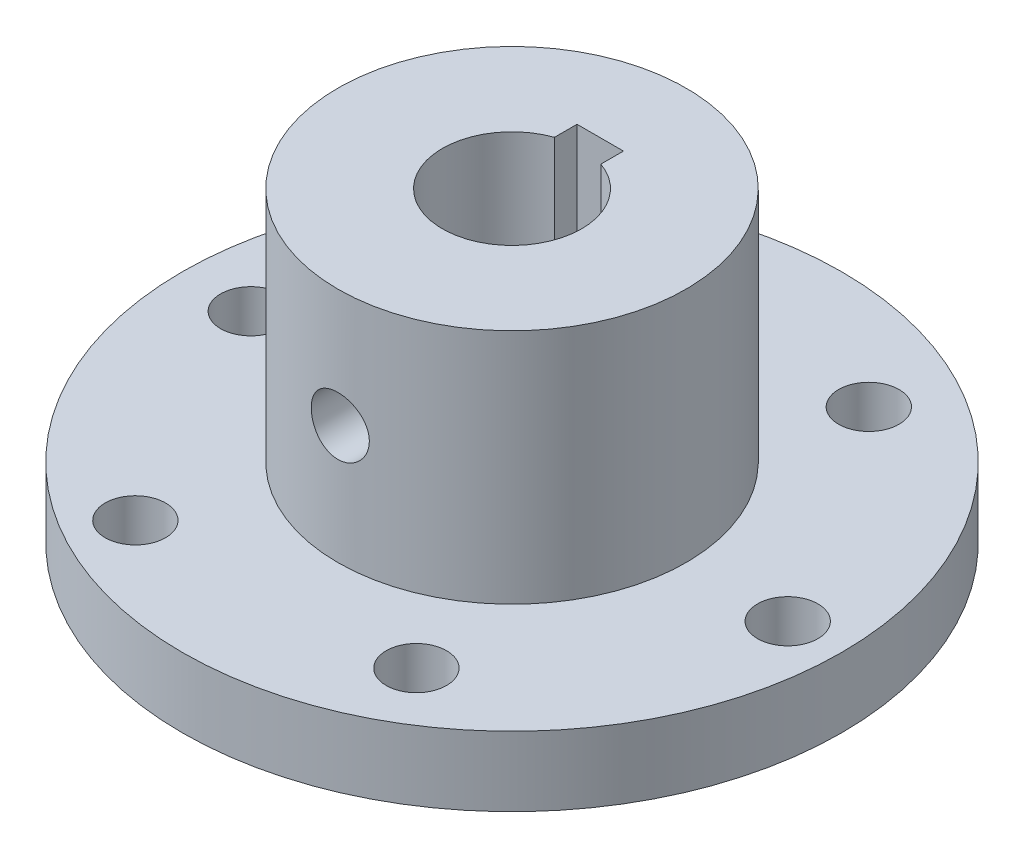
SolidWorks part; units mm, degrees
ref_plane "前视基准面" through (0, 0, 0) normal (0, 0, 1) x (1, 0, 0)
ref_plane "上视基准面" through (0, 0, 0) normal (0, 1, 0) x (1, 0, 0)
ref_plane "右视基准面" through (0, 0, 0) normal (1, 0, 0) x (0, 0, -1)
sketch "Sketch1" plane through (0, 0, 0) normal (1, 0, 0) x (0, 0, -1)
  line L0 (6, 0) -> (28.4, 0)
  line L1 (28.4, 0) -> (28.4, 6)
  line L2 (28.4, 6) -> (15, 6)
  line L3 (15, 6) -> (15, 26.4)
  line L4 (15, 26.4) -> (6, 26.4)
  line L5 (6, 26.4) -> (6, 0)
  line L6 (0, 21.7671) -> (0, -3.5767) construction
  dimension "D1" = 6
  dimension "D2" = 15
  dimension "D3" = 28.4
  dimension "D4" = 6
  dimension "D5" = 20.4
revolve "Revolve1" add sketch "Sketch1" angle 360 about L6
sketch "Sketch3" plane through (0, 6, 0) normal (0, 1, 0) x (1, 0, 0)
  circle A0 centre (0, 0) radius 22.5 construction
  circle A1 centre (-22.5, 0) radius 2.6
  circle A2 centre (11.25, 19.4856) radius 2.6
  circle A3 centre (11.25, -19.4856) radius 2.6
  circle A8 centre (0, 0) radius 23.75 construction
  circle A9 centre (23.75, 0) radius 2.6
  circle A10 centre (-11.875, -20.5681) radius 2.6
  circle A11 centre (-11.875, 20.5681) radius 2.6
  dimension "D1" = 45
  dimension "D2" = 5.2
  dimension "D4" = 47.5
  dimension "D5" = 3
  dimension "D3" = 3
extrude "Cut-Extrude2" cut sketch "Sketch3" against normal up to next
sketch "Sketch4" plane through (0, 26.4, 0) normal (0, 1, 0) x (1, 0, 0)
  line L0 (0, -19.1286) -> (0, 23.5515) construction
  line L1 (-5.6768, 7.6) -> (7.5958, 7.6) construction
  line L2 (-2, 7.6) -> (-2, 5.6569)
  line L3 (-2, 7.6) -> (2, 7.6)
  line L6 (-3.2061, 6) -> (6.6126, 6) construction
  line L7 (2, 7.6) -> (2, 5.6569)
  circle A0 centre (0, 0) radius 6 construction
  arc A1 (2, 5.6569) -> (-2, 5.6569) centre (0, 0) ccw
  point P10 (0, 7.6)
  point P16 (0, 7.6)
  dimension "D1" = 2
  dimension "D2" = 1.6
extrude "Cut-Extrude3" cut sketch "Sketch4" against normal up to next
ref_plane "Plane1" through (0, 0, 15) normal (0, 0, 1) x (1, 0, 0)
hole_wizard "M6 Tapped Hole2" positions "3DSketch4" profile "Sketch9" tap size "M6" standard "DIN"
sketch3d "3DSketch4"
  line L0 (0, 0, 0) -> (0, 16.2, 0) construction
  line L1 (0, 16.2, 0) -> (0, 16.2, 15) construction
  point P0 (0, 16.2, 15)
  dimension "D1" = 16.2
sketch "Sketch9" plane through (0, 16.2, 15) normal (1, 0, 0) x (0, -1, 0)
  line L0 (0, 0) -> (0, 9)
  line L1 (0, 9) -> (2.5, 9)
  line L2 (2.5, 9) -> (2.5, 0)
  line L5 (2.5, 0) -> (0, 0)
  line L11 (0, -6.35) -> (0, 107.95) construction
  dimension "Thru Tap Drill Dia." = 5
  dimension "Thru Tap Drill Depth" = 9
cosmetic thread "Hole Thread1" parameters "D2"=6
